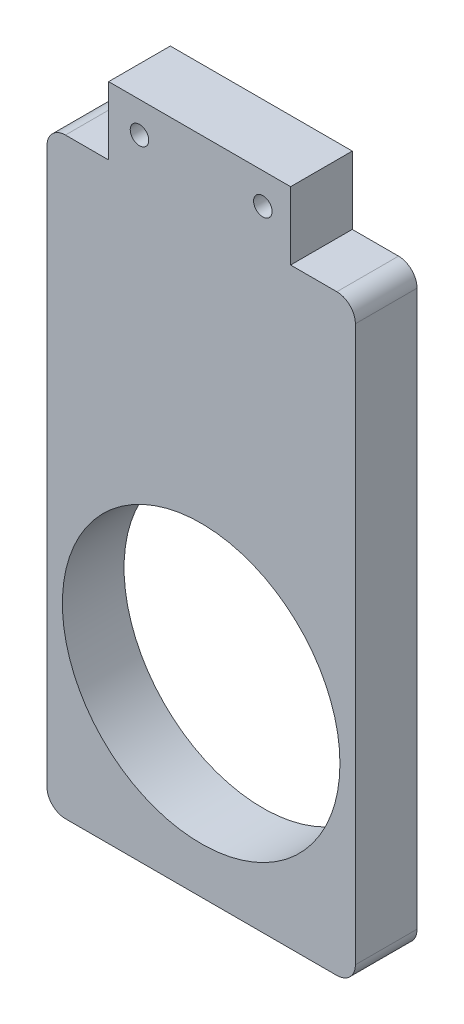
SolidWorks part; units mm, degrees
ref_plane "Ön Düzlem" through (0, 0, 0) normal (0, 0, 1) x (1, 0, 0)
ref_plane "Üst Düzlem" through (0, 0, 0) normal (0, 1, 0) x (1, 0, 0)
ref_plane "Sağ Düzlem" through (0, 0, 0) normal (1, 0, 0) x (0, 0, -1)
ref_plane "Düzlem1" through (0, 0, 10) normal (0, 0, 1) x (1, 0, 0)
sketch "Çizim1" plane through (0, 0, 10) normal (0, 0, 1) x (1, 0, 0)
  line L0 (3, -38) -> (47, -38)
  line L2 (50, -35) -> (50, 55)
  line L3 (47, 58) -> (39.5, 58)
  line L4 (39.5, 58) -> (39.5, 69)
  line L5 (39.5, 69) -> (10, 69)
  line L6 (10, 69) -> (10, 58)
  line L7 (10, 58) -> (3, 58)
  line L8 (0, 55) -> (0, -35)
  circle A0 centre (15, 64) radius 1.5
  arc A1 (0, -35) -> (3, -38) centre (3, -35) ccw
  circle A2 centre (25, -8) radius 22.5
  arc A3 (47, -38) -> (50, -35) centre (47, -35) ccw
  arc A4 (50, 55) -> (47, 58) centre (47, 55) ccw
  arc A5 (3, 58) -> (0, 55) centre (3, 55) ccw
  circle A11 centre (35, 64) radius 1.5
  dimension "D1" = 29.5
  dimension "D5" = 30
  dimension "D2" = 11
  dimension "D3" = 5
  dimension "D4" = 5
  dimension "D6" = 25
extrude "Yükseklik-Ekstrüzyon1" add sketch "Çizim1" against normal blind 10
